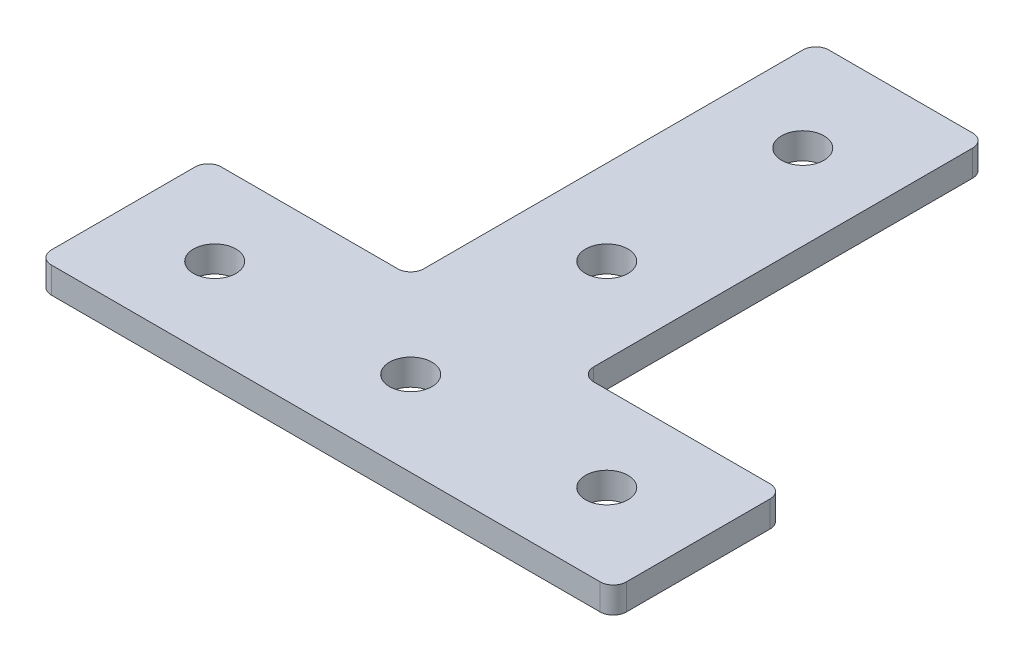
SolidWorks part; units mm, degrees
ref_plane "Front Plane" through (0, 0, 0) normal (0, 0, 1) x (1, 0, 0)
ref_plane "Top Plane" through (0, 0, 0) normal (0, 1, 0) x (1, 0, 0)
ref_plane "Right Plane" through (0, 0, 0) normal (1, 0, 0) x (0, 0, -1)
sketch "Sketch1" plane through (0, 0, 0) normal (0, 1, 0) x (1, 0, 0)
  line L2 (-44, 13) -> (-44, -13)
  line L3 (-44, -13) -> (44, -13)
  line L4 (44, 13) -> (44, -13)
  line L5 (44, 13) -> (13, 13)
  line L6 (-44, 13) -> (-13, 13)
  line L10 (-13, 13) -> (-13, 75)
  line L11 (-13, 75) -> (13, 75)
  line L12 (13, 13) -> (13, 75)
  line L13 (-44, 0) -> (44, 0) construction
  point P0 (0, 0)
  point P6 (0, 0)
  point P13 (0, 0)
  dimension "D1" = 26
  dimension "D2" = 88
  dimension "D3" = 26
  dimension "D4" = 88
extrude "Boss-Extrude1" add sketch "Sketch1" along normal blind 4
sketch "Sketch3" plane through (0, 4, 0) normal (0, 1, 0) x (1, 0, 0)
  line L0 (13, 75) -> (-13, 75) construction
  circle A0 centre (0, 0) radius 3.25
  circle A1 centre (30, 0) radius 3.25
  circle A2 centre (-30, 0) radius 3.25
  circle A3 centre (0, 60) radius 3.25
  circle A4 centre (0, 30) radius 3.25
  dimension "D1" = 6.5
  dimension "D4" = 6.5
  dimension "D5" = 15
  dimension "D2" = 2
  dimension "D3" = 2
  dimension "D6" = 2
extrude "Cut-Extrude1" cut sketch "Sketch3" against normal through all
fillet "Fillet1" radius 2 8 edges at (-44, 2, 13) (-44, 2, -13) (-13, 2, -13) (44, 2, 13) (44, 2, -13) (13, 2, -13) (13, 2, -75) (-13, 2, -75)
